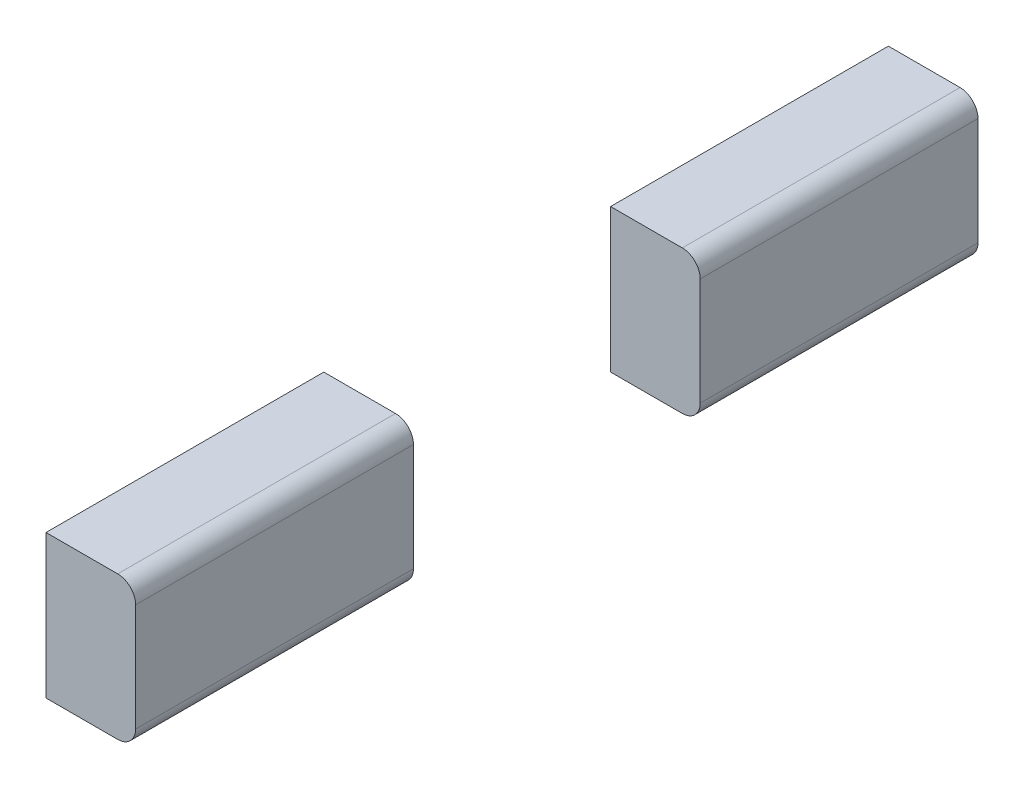
SolidWorks part; units mm, degrees
material "Massless"
ref_plane "Front Plane" through (0, 0, 0) normal (0, 0, 1) x (1, 0, 0)
ref_plane "Top Plane" through (0, 0, 0) normal (0, 1, 0) x (1, 0, 0)
ref_plane "Right Plane" through (0, 0, 0) normal (1, 0, 0) x (0, 0, -1)
sketch "Sketch1" plane through (0, 0, 0) normal (0, 0, 1) x (1, 0, 0)
  line L0 (0, 0) -> (0, 101.6)
  line L4 (0, 101.6) -> (63.5, 101.6)
  line L5 (63.5, 101.6) -> (63.5, 0)
  line L6 (63.5, 0) -> (0, 0)
  dimension "D1" = 63.5
  dimension "D2" = 101.6
extrude "Boss-Extrude1" add sketch "Sketch1" along normal blind 596.9
fillet "Fillet1" radius 12.7 2 edges at (63.5, 0, 298.45) (63.5, 101.6, 298.45)
sketch "Sketch2" plane through (63.5, 0, 0) normal (1, 0, 0) x (0, 0, -1)
  line L0 (-596.9, 101.6) -> (0, 101.6) construction
  line L1 (-400.05, 101.6) -> (-196.85, 101.6)
  line L2 (-400.05, 101.6) -> (-400.05, 0)
  line L3 (-400.05, 0) -> (-196.85, 0)
  line L4 (-196.85, 101.6) -> (-196.85, 0)
  line L5 (0, 0) -> (-596.9, 0) construction
  line L8 (0, 88.9) -> (-596.9, 88.9) construction
  point P10 (-298.45, 88.9)
  point P11 (-298.45, 101.6)
  dimension "D1" = 203.2
extrude "Cut-Extrude1" cut sketch "Sketch2" against normal through all
